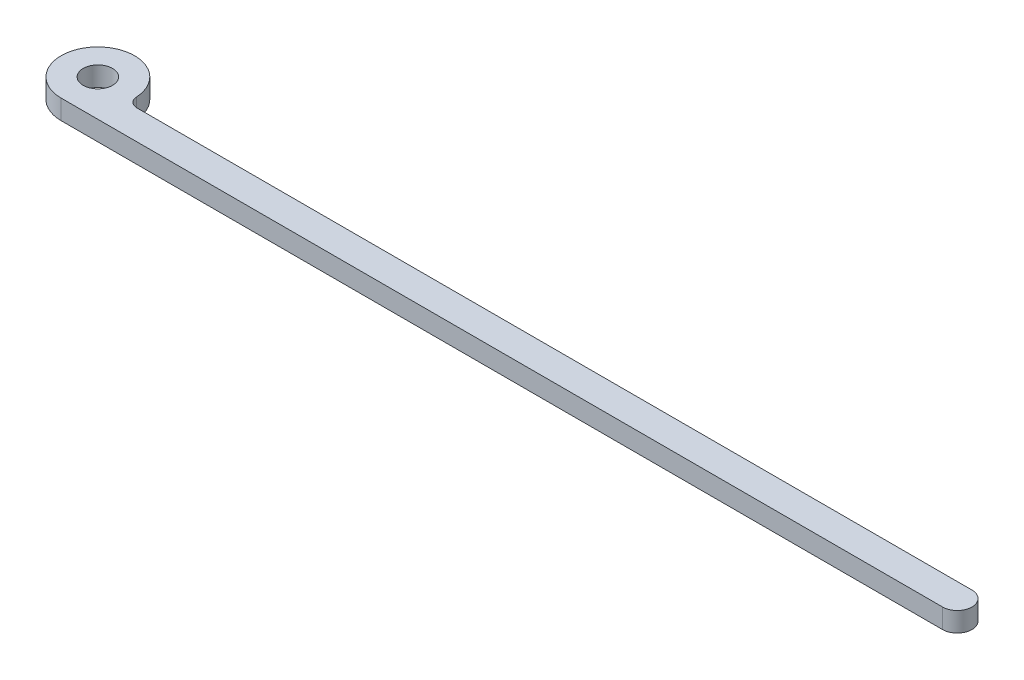
SolidWorks part; units mm, degrees
ref_plane "Front" through (0, 0, 0) normal (0, 0, 1) x (1, 0, 0)
ref_plane "Top" through (0, 0, 0) normal (0, 1, 0) x (1, 0, 0)
ref_plane "Right" through (0, 0, 0) normal (1, 0, 0) x (0, 0, -1)
sketch "Sketch1" plane through (0, 0, 0) normal (0, 1, 0) x (1, 0, 0)
  line L0 (0, -7.5) -> (180, -7.5)
  line L1 (180, -1.5) -> (7.3485, -1.5)
  circle A0 centre (0, 0) radius 3
  arc A1 (7.3485, -1.5) -> (0, -7.5) centre (0, 0) ccw
  arc A2 (180, -7.5) -> (180, -1.5) centre (180, -4.5) ccw
  dimension "D1" = 6
  dimension "D2" = 15
  dimension "D3" = 6
  dimension "D4" = 180
extrude "Boss-Extrude1" add sketch "Sketch1" along normal mid plane 4
fillet "Fillet1" radius 2 1 edges at (7.3485, 0, 1.5)
